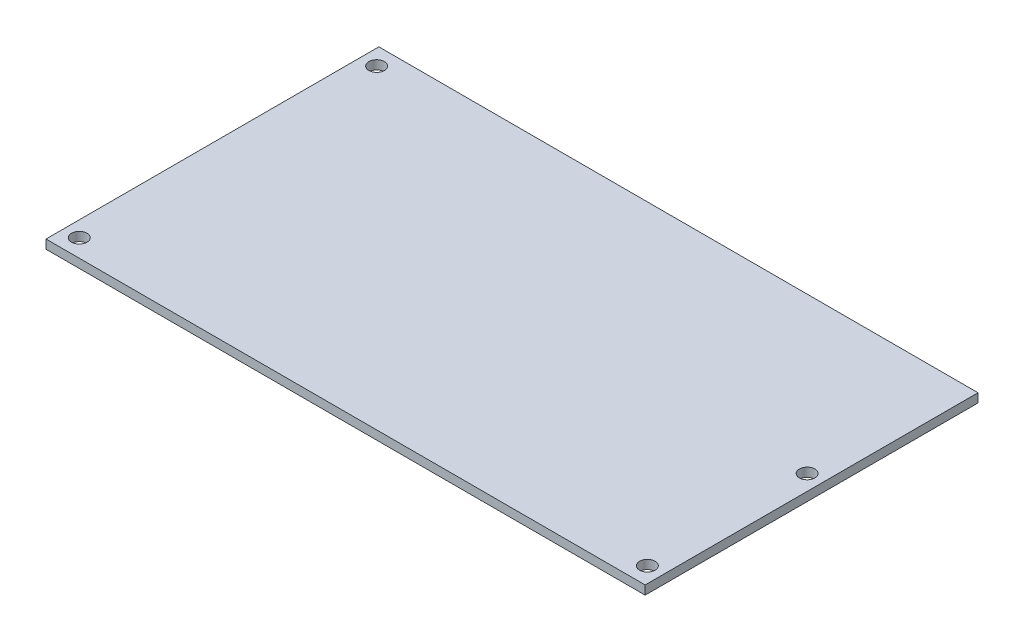
SolidWorks part; units mm, degrees
ref_plane "Спереди" through (0, 0, 0) normal (0, 0, 1) x (1, 0, 0)
ref_plane "Сверху" through (0, 0, 0) normal (0, 1, 0) x (1, 0, 0)
ref_plane "Справа" through (0, 0, 0) normal (1, 0, 0) x (0, 0, -1)
sketch "Эскиз1" plane through (0, 0, 0) normal (0, 1, 0) x (1, 0, 0)
  line L0 (-64, 33.5) -> (-64, 0) construction
  line L1 (-67.5, 37.5) -> (67.5, 37.5)
  line L2 (-67.5, 37.5) -> (-67.5, -37.5)
  line L3 (-67.5, -37.5) -> (67.5, -37.5)
  line L4 (67.5, 37.5) -> (67.5, -37.5)
  line L5 (-67.5, 37.5) -> (67.5, -37.5) construction
  line L6 (-67.5, -37.5) -> (67.5, 37.5) construction
  line L7 (-64, 0) -> (-64, -33.5) construction
  line L8 (-64, -33.5) -> (0, -33.5) construction
  line L9 (0, -33.5) -> (64, -33.5) construction
  line L10 (64, -33.5) -> (64, 2.5) construction
  circle A0 centre (-64, -33.5) radius 1.75
  circle A1 centre (-64, 33.5) radius 1.75
  circle A2 centre (64, -33.5) radius 1.75
  circle A3 centre (64, 2.5) radius 1.75
  point P0 (0, 0)
  dimension "D3" = 3.5
  dimension "D1" = 135
  dimension "D2" = 75
  dimension "D4" = 128
  dimension "D5" = 67
  dimension "D6" = 36
extrude "База" add sketch "Эскиз1" along normal blind 2
